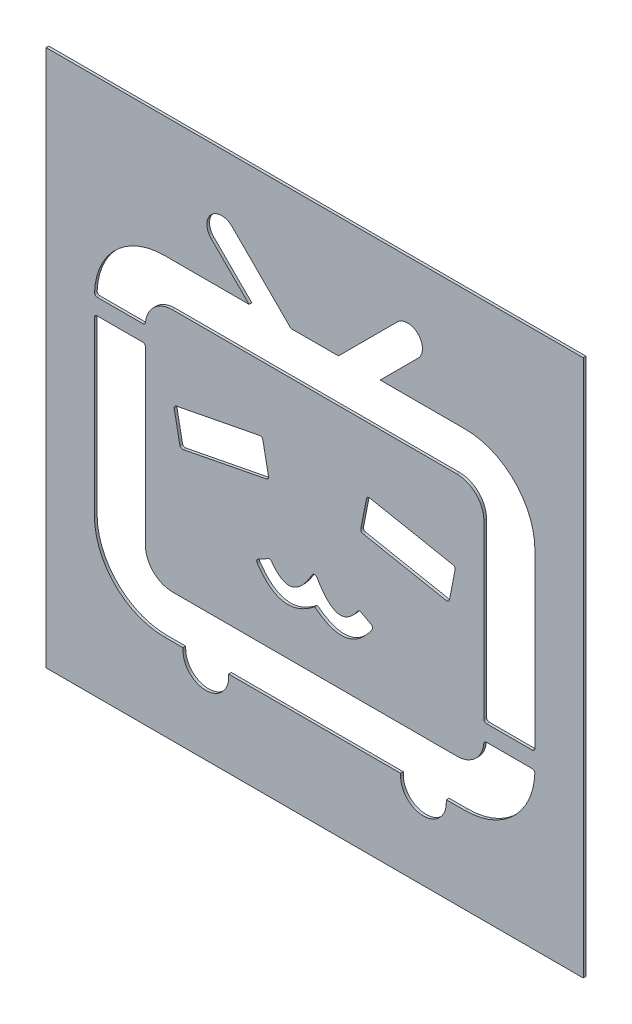
SolidWorks part; units mm, degrees
ref_plane "前视基准面" through (0, 0, 0) normal (0, 0, 1) x (1, 0, 0)
ref_plane "上视基准面" through (0, 0, 0) normal (0, 1, 0) x (1, 0, 0)
ref_plane "右视基准面" through (0, 0, 0) normal (1, 0, 0) x (0, 0, -1)
sketch "草图1" plane through (0, 0, 0) normal (0, 0, 1) x (1, 0, 0)
  line L1 (0, 0) -> (200, 0)
  line L2 (0, 0) -> (0, -200)
  line L3 (0, -200) -> (200, -200)
  line L4 (200, 0) -> (200, -200)
extrude "Background" add sketch "草图1" along normal blind 1
sketch "草图2" plane through (0, 0, 1) normal (0, 0, 1) x (1, 0, 0)
  line L0 (200, 0) -> (0, 0) construction
  line L1 (44, -45) -> (75.5944, -45)
  line L3 (44, -168) -> (51, -168)
  line L4 (182, -71) -> (182, -136)
  line L5 (0, -200) -> (200, -200) construction
  line L6 (0, 0) -> (0, -200) construction
  line L7 (200, -200) -> (200, 0) construction
  line L8 (124.4056, -45) -> (156, -45)
  line L9 (47, -61) -> (153, -61)
  line L11 (47, -152) -> (153, -152)
  line L12 (163, -71) -> (163, -136)
  line L13 (75.5944, -45) -> (61.4835, -30.8891)
  line L14 (91.1508, -45) -> (69.2617, -23.1109)
  line L15 (59.5, -166) -> (59.5, -169) construction
  line L16 (108.8492, -45) -> (130.7383, -23.1109)
  line L17 (124.4056, -45) -> (138.5165, -30.8891)
  line L18 (91.1508, -45) -> (108.8492, -45)
  line L19 (68, -168) -> (68, -169)
  line L20 (51, -168) -> (51, -169)
  line L21 (140.5, -168) -> (140.5, -169) construction
  line L22 (149, -168) -> (149, -169)
  line L23 (132, -168) -> (132, -169)
  line L24 (68, -168) -> (132, -168)
  line L25 (149, -168) -> (156, -168)
  line L36 (47.5195, -91.5358) -> (80.5195, -85.1212)
  line L37 (47.5195, -91.5358) -> (50, -104.2969)
  line L38 (80.5195, -85.1212) -> (83, -97.8824)
  line L39 (50, -104.2969) -> (83, -97.8824)
  line L40 (119.4805, -84.7963) -> (152.4805, -91.2109)
  line L41 (119.4805, -84.7963) -> (117, -97.5575)
  line L42 (152.4805, -91.2109) -> (150, -103.972)
  line L43 (117, -97.5575) -> (150, -103.972)
  line L44 (78, -126) -> (83.5, -123)
  line L45 (116.5, -123) -> (122, -126)
  line L46 (100, -152) -> (100, -99.173) construction
  line L47 (37, -77) -> (37, -142)
  line L52 (18, -77) -> (18, -142)
  line L53 (18, -71) -> (18, -77) construction
  line L54 (18, -71) -> (37, -71)
  line L56 (18, -77) -> (37, -77)
  line L57 (37, -71) -> (37, -77) construction
  line L58 (182, -136) -> (182, -142) construction
  line L59 (163, -142) -> (182, -142)
  line L61 (163, -136) -> (182, -136)
  line L63 (163, -136) -> (163, -142) construction
  arc A0 (18, -142) -> (44, -168) centre (44, -142) ccw
  arc A1 (156, -168) -> (182, -142) centre (156, -142) ccw
  arc A2 (156, -45) -> (182, -71) centre (156, -71) cw
  arc A3 (44, -45) -> (18, -71) centre (44, -71) ccw
  arc A4 (37, -142) -> (47, -152) centre (47, -142) ccw
  arc A5 (153, -152) -> (163, -142) centre (153, -142) ccw
  arc A6 (153, -61) -> (163, -71) centre (153, -71) cw
  arc A7 (47, -61) -> (37, -71) centre (47, -71) ccw
  arc A9 (69.2617, -23.1109) -> (61.4835, -30.8891) centre (65.3726, -27) ccw
  arc A11 (138.5165, -30.8891) -> (130.7383, -23.1109) centre (134.6274, -27) ccw
  arc A13 (51, -169) -> (68, -169) centre (59.5, -169) ccw
  arc A15 (132, -169) -> (149, -169) centre (140.5, -169) ccw
  spline S0 degree 2 poles (83.5, -123) (91.45, -135.2029) (100, -118.8125) knots 0 0 0 1 1 1
  spline S1 degree 2 poles (78, -126) (87.1598, -140.5695) (100, -130.3154) knots 0 0 0 1 1 1
  spline S2 degree 2 poles (116.5, -123) (108.55, -135.2029) (100, -118.8125) knots 0 0 0 1 1 1
  spline S3 degree 2 poles (122, -126) (112.8402, -140.5695) (100, -130.3154) knots 0 0 0 1 1 1
  point P34 (76.6863, -38.3137)
  point P39 (59.5, -167.5)
  point P41 (123.3137, -38.3137)
  point P53 (140.5, -167.5)
  dimension "D5" = 26
  dimension "D10" = 10
  dimension "D12" = 27
  dimension "D11" = 27
  dimension "D14" = 59.5
  dimension "D15" = 59.5
  dimension "D17" = 13
  dimension "D1" = 45
  dimension "D2" = 32
  dimension "D4" = 18
  dimension "D6" = 6
  dimension "D7" = 37
  dimension "D8" = 61
  dimension "D9" = 48
  dimension "D13" = 2
  dimension "D18" = 79
  dimension "D20" = 33
  dimension "D21" = 33
  dimension "D22" = 13
  dimension "D23" = 13
  dimension "D24" = 41
  dimension "D27" = 52
  dimension "D29" = 52
  dimension "D30" = 46.5
  dimension "D32" = 29
  dimension "D33" = 29
  dimension "D34" = 26
  dimension "D35" = 26
  dimension "D36" = 17.5
  dimension "D37" = 17.5
  dimension "D38" = 24
  dimension "D39" = 24
extrude "Logo" cut sketch "草图2" against normal blind 10
fillet "R" radius 1 21 edges at (122, -126, 0.5) (116.5, -123, 0.5) (100, -118.8125, 0.5) (78, -126, 0.5) (83.5, -123, 0.5) (117, -97.5575, 0.5) (150, -103.972, 0.5) (152.4805, -91.2109, 0.5) (119.4805, -84.7963, 0.5) (50, -104.2969, 0.5) (83, -97.8824, 0.5) (80.5195, -85.1212, 0.5) (47.5195, -91.5358, 0.5) (163, -142, 0.5) (182, -142, 0.5) (182, -136, 0.5) (163, -136, 0.5) (18, -71, 0.5) (37, -71, 0.5) (37, -77, 0.5) (18, -77, 0.5)
